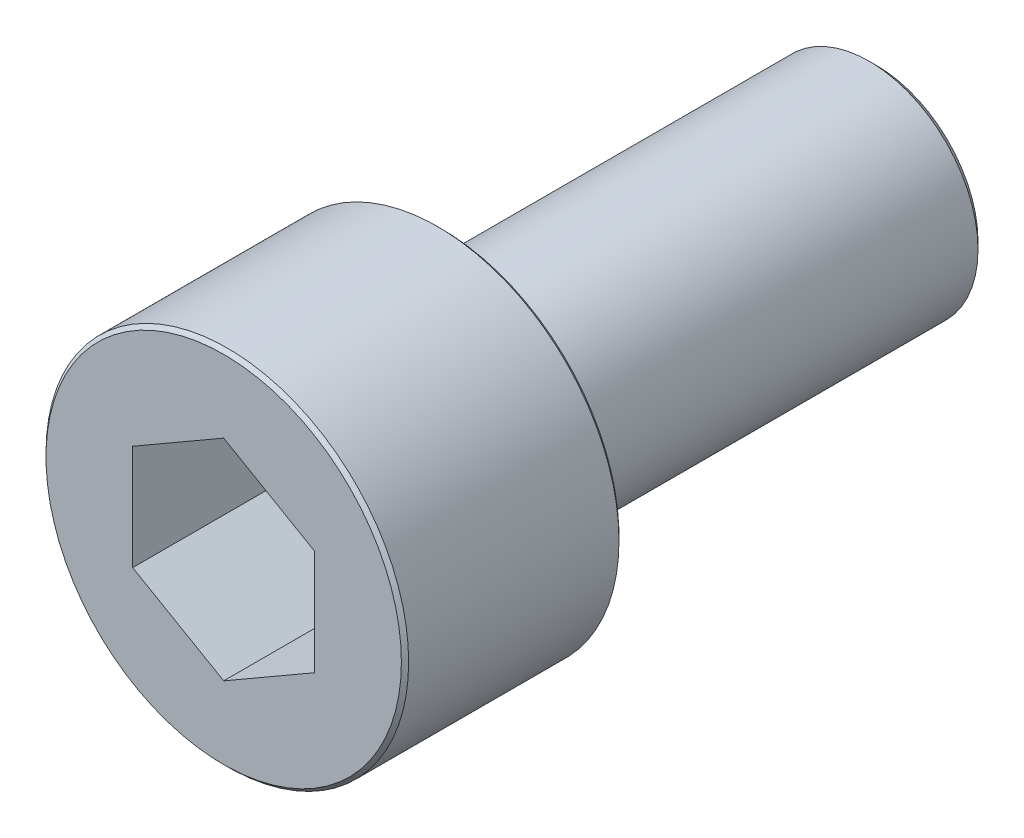
SolidWorks part; units mm, degrees
ref_plane "前视基准面" through (0, 0, 0) normal (0, 0, 1) x (1, 0, 0)
ref_plane "上视基准面" through (0, 0, 0) normal (0, 1, 0) x (1, 0, 0)
ref_plane "右视基准面" through (0, 0, 0) normal (1, 0, 0) x (0, 0, -1)
other "Configuration Table"
sketch "草图1" plane through (0, 0, 0) normal (0, 1, 0) x (1, 0, 0)
  line L0 (5, -12) -> (0, -12)
  line L1 (0, -12) -> (0, -18)
  line L2 (0, -18) -> (5, -18)
  line L3 (5, -18) -> (5, -12)
  line L4 (0, -12) -> (0, -18) construction
revolve "旋转1" add sketch "草图1" angle 360 about L4
sketch "草图2" plane through (0, 0, 12) normal (0, 0, -1) x (-1, 0, 0)
  circle A0 centre (0, 0) radius 3
extrude "凸台-拉伸1" add sketch "草图2" along normal blind 12
sketch "草图3" plane through (0, 0, 18) normal (0, 0, 1) x (1, 0, 0)
  line L0 (-2.51, -1.4491) -> (0, -2.8983)
  line L1 (0, -2.8983) -> (2.51, -1.4491)
  line L2 (2.51, -1.4491) -> (2.51, 1.4491)
  line L3 (2.51, 1.4491) -> (0, 2.8983)
  line L4 (0, 2.8983) -> (-2.51, 1.4491)
  line L5 (-2.51, 1.4491) -> (-2.51, -1.4491)
extrude "切除-拉伸1" cut sketch "草图3" against normal blind 4.5
chamfer "倒角1" distance 0.1 angle 45 2 edges at (5, 0, 12) (5, 0, 18)
chamfer "倒角2" distance 0.2 angle 45 1 edges at (-3, 0, 0)
